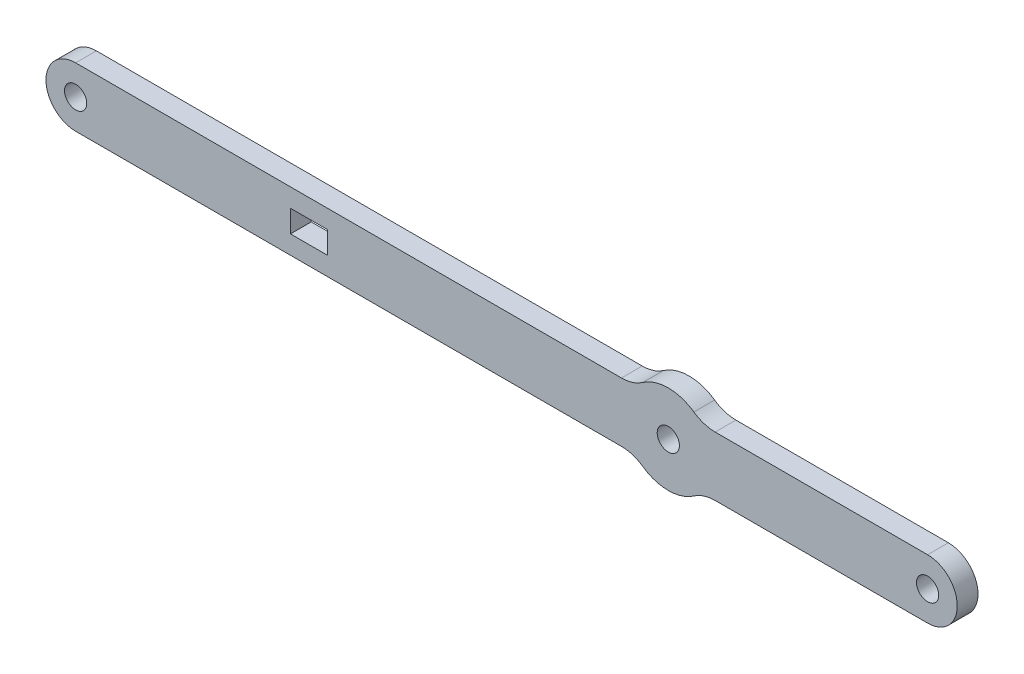
SolidWorks part; units mm, degrees
material "pla filament"
ref_plane "Ön Düzlem" through (0, 0, 0) normal (0, 0, 1) x (1, 0, 0)
ref_plane "Üst Düzlem" through (0, 0, 0) normal (0, 1, 0) x (1, 0, 0)
ref_plane "Sağ Düzlem" through (0, 0, 0) normal (1, 0, 0) x (0, 0, -1)
sketch "Sketch1" plane through (0, 0, 0) normal (0, 0, 1) x (1, 0, 0)
  line L0 (0, 0) -> (115, 0) construction
  line L1 (0.0062, 4) -> (75.5279, 4)
  line L2 (-0.0071, -4) -> (75.5279, -4)
  line L3 (84.4721, 4) -> (115, 4)
  line L4 (84.4721, -4) -> (115, -4)
  line L6 (29, -1.5) -> (34, -1.5)
  line L7 (29, -1.5) -> (29, 1.5)
  line L8 (29, 1.5) -> (34, 1.5)
  line L9 (34, -1.5) -> (34, 1.5)
  line L10 (29, -1.5) -> (34, 1.5) construction
  line L11 (29, 1.5) -> (34, -1.5) construction
  arc A0 (0.0062, 4) -> (-0.0071, -4) centre (0, 0) ccw
  arc A1 (115, -4) -> (115, 4) centre (115, 0) ccw
  circle A2 centre (80, 0) radius 1.5
  circle A3 centre (115, 0) radius 1.5
  circle A4 centre (0, 0) radius 1.5
  arc A5 (84.4721, 4) -> (75.5279, 4) centre (80, 0) ccw
  arc A6 (75.5279, -4) -> (84.4721, -4) centre (80, 0) ccw
  point P3 (57.5, 0)
  point P14 (31.5, 0)
  point P23 (-4, 0.0066)
  dimension "D3" = 3
  dimension "D5" = 3
  dimension "D6" = 3
  dimension "D7" = 12
  dimension "D1" = 115
  dimension "D2" = 35
  dimension "D4" = 8
  dimension "D8" = 38
  dimension "D9" = 5
  dimension "D10" = 3
extrude "Boss-Extrude1" add sketch "Sketch1" along normal blind 2.8
fillet "Fillet1" radius 5 4 edges at (84.4721, -4, 1.4) (75.5279, -4, 1.4) (75.5279, 4, 1.4) (84.4721, 4, 1.4)
